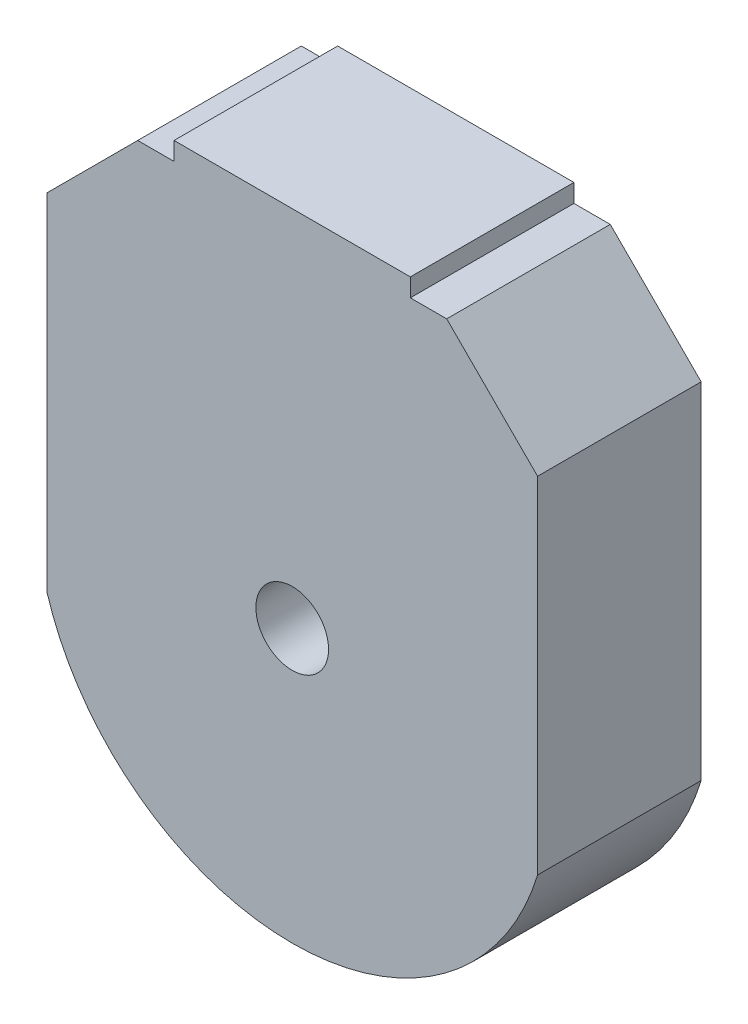
SolidWorks part; units mm, degrees
ref_plane "Front" through (0, 0, 0) normal (0, 0, 1) x (1, 0, 0)
ref_plane "Top" through (0, 0, 0) normal (0, 1, 0) x (1, 0, 0)
ref_plane "Right" through (0, 0, 0) normal (1, 0, 0) x (0, 0, -1)
sketch "Esquisse1" plane through (0, 0, 0) normal (0, 0, 1) x (1, 0, 0)
  line L0 (6.5, 35) -> (-6.5, 35)
  line L1 (0, 0) -> (-13.5, 0) construction
  line L2 (0, 0) -> (0, 35) construction
  line L3 (0, 35) -> (-13.5, 35) construction
  line L4 (-13.5, 0) -> (-13.5, 35) construction
  line L5 (-6.5, 35) -> (-6.5, 34)
  line L6 (-6.5, 34) -> (-8.5, 34)
  line L7 (-8.5, 34) -> (-13.5, 29)
  line L8 (-13.5, 29) -> (-13.5, 10)
  line L9 (13.5, 29) -> (13.5, 10)
  line L10 (8.5, 34) -> (13.5, 29)
  line L11 (6.5, 34) -> (8.5, 34)
  line L12 (6.5, 35) -> (6.5, 34)
  arc A0 (-13.5, 10) -> (13.5, 10) centre (0, 14.1125) ccw
  circle A2 centre (0, 15) radius 2
  dimension "D10" = 4
  dimension "D1" = 35
  dimension "D2" = 13.5
  dimension "D3" = 1
  dimension "D4" = 5
  dimension "D5" = 5
  dimension "D6" = 6.5
  dimension "D7" = 19
  dimension "D8" = 0
  dimension "D9" = 15
extrude "Boss.-Extru.2" add sketch "Esquisse1" along normal blind 9
